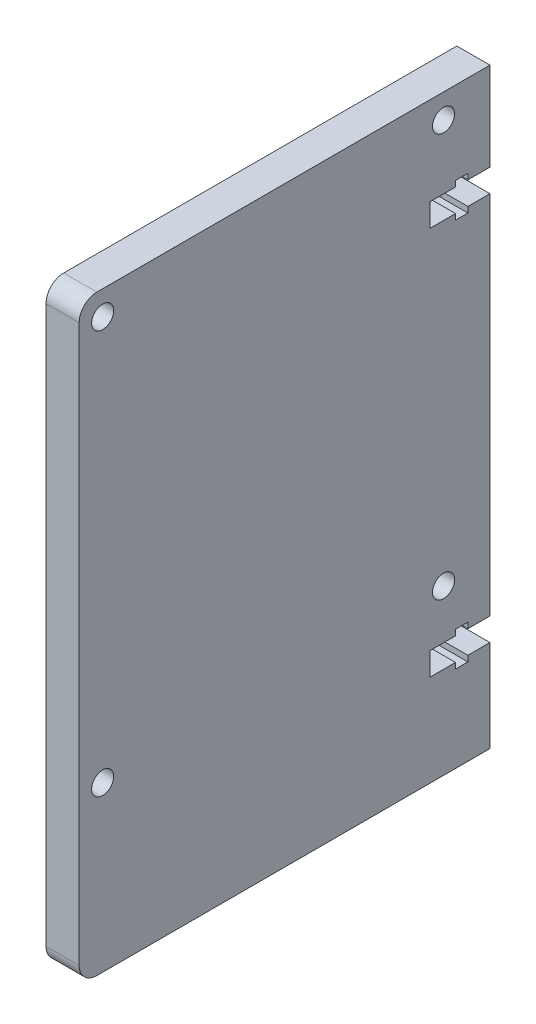
SolidWorks part; units mm, degrees
ref_plane "Front Plane" through (0, 0, 0) normal (0, 0, 1) x (1, 0, 0)
ref_plane "Top Plane" through (0, 0, 0) normal (0, 1, 0) x (1, 0, 0)
ref_plane "Right Plane" through (0, 0, 0) normal (1, 0, 0) x (0, 0, -1)
sketch "Sketch1" plane through (0, 0, 0) normal (1, 0, 0) x (0, 0, -1)
  line L1 (-191.8464, 60.2721) -> (-132.7914, 60.2721)
  line L2 (-191.8464, 60.2721) -> (-191.8464, -24.8179)
  line L3 (-191.8464, -24.8179) -> (-132.7914, -24.8179)
  line L4 (-132.7914, 60.2721) -> (-132.7914, -24.8179)
  point P0 (-138.2712, 17.7271)
  dimension "D1" = 85.09
  dimension "D2" = 59.055
extrude "Boss-Extrude1" add sketch "Sketch1" along normal blind 4.7625
sketch "Sketch2" plane through (4.7625, 0, 0) normal (1, 0, 0) x (0, 0, -1)
  circle A0 centre (-188.4664, -1.2279) radius 1.5875
  circle A1 centre (-139.4664, -1.2279) radius 1.5875
  circle A2 centre (-139.4664, 56.7721) radius 1.5875
  circle A3 centre (-188.4664, 56.7721) radius 1.5875
  dimension "D1" = 3.175
extrude "Cut-Extrude1" cut sketch "Sketch2" against normal up to next
sketch "Sketch3" plane through (0, 0, 0) normal (-1, 0, 0) x (0, 0, 1)
  line L1 (132.7914, -24.8179) -> (132.7914, 60.2721) construction
  line L2 (132.7914, 47.5721) -> (135.9664, 47.5721)
  line L3 (132.7914, 47.5721) -> (132.7914, 44.2701)
  line L4 (132.7914, 44.2701) -> (135.9664, 44.2701)
  line L6 (132.7914, -8.3079) -> (135.9664, -8.3079)
  line L7 (141.4274, 47.5721) -> (141.4274, 44.2701)
  line L8 (132.7914, 60.2721) -> (191.8464, 60.2721) construction
  line L9 (137.7444, 44.2701) -> (141.4274, 44.2701)
  line L10 (137.7444, 47.5721) -> (137.7444, 48.3976)
  line L11 (135.9664, 43.4446) -> (137.7444, 43.4446)
  line L12 (135.9664, 43.4446) -> (135.9664, 44.2701)
  line L13 (132.7914, -8.3079) -> (132.7914, -11.6099)
  line L14 (135.9664, 48.3976) -> (137.7444, 48.3976)
  line L15 (137.7444, 43.4446) -> (137.7444, 44.2701)
  line L16 (132.7914, -11.6099) -> (135.9664, -11.6099)
  line L17 (141.4274, -8.3079) -> (141.4274, -11.6099)
  line L18 (137.7444, -11.6099) -> (141.4274, -11.6099)
  line L19 (137.7444, -8.3079) -> (137.7444, -7.4824)
  line L20 (135.9664, -12.4354) -> (137.7444, -12.4354)
  line L21 (135.9664, -12.4354) -> (135.9664, -11.6099)
  line L22 (135.9664, -7.4824) -> (137.7444, -7.4824)
  line L23 (137.7444, -12.4354) -> (137.7444, -11.6099)
  line L24 (137.7444, -8.3079) -> (141.4274, -8.3079)
  line L25 (135.9664, -8.3079) -> (135.9664, -7.4824)
  line L29 (137.7444, 47.5721) -> (141.4274, 47.5721)
  line L30 (135.9664, 47.5721) -> (135.9664, 48.3976)
  point P8 (136.8554, 45.9211)
  point P21 (136.8554, -9.9589)
  dimension "D1" = 12.7
  dimension "D2" = 3.302
  dimension "D3" = 8.636
  dimension "D4" = 1.778
  dimension "D5" = 4.953
  dimension "D6" = 2
extrude "Cut-Extrude2" cut sketch "Sketch3" against normal through all
fillet "Fillet1" radius 2.54 2 edges at (2.3813, -24.8179, 191.8464) (2.3813, 60.2721, 191.8464)
